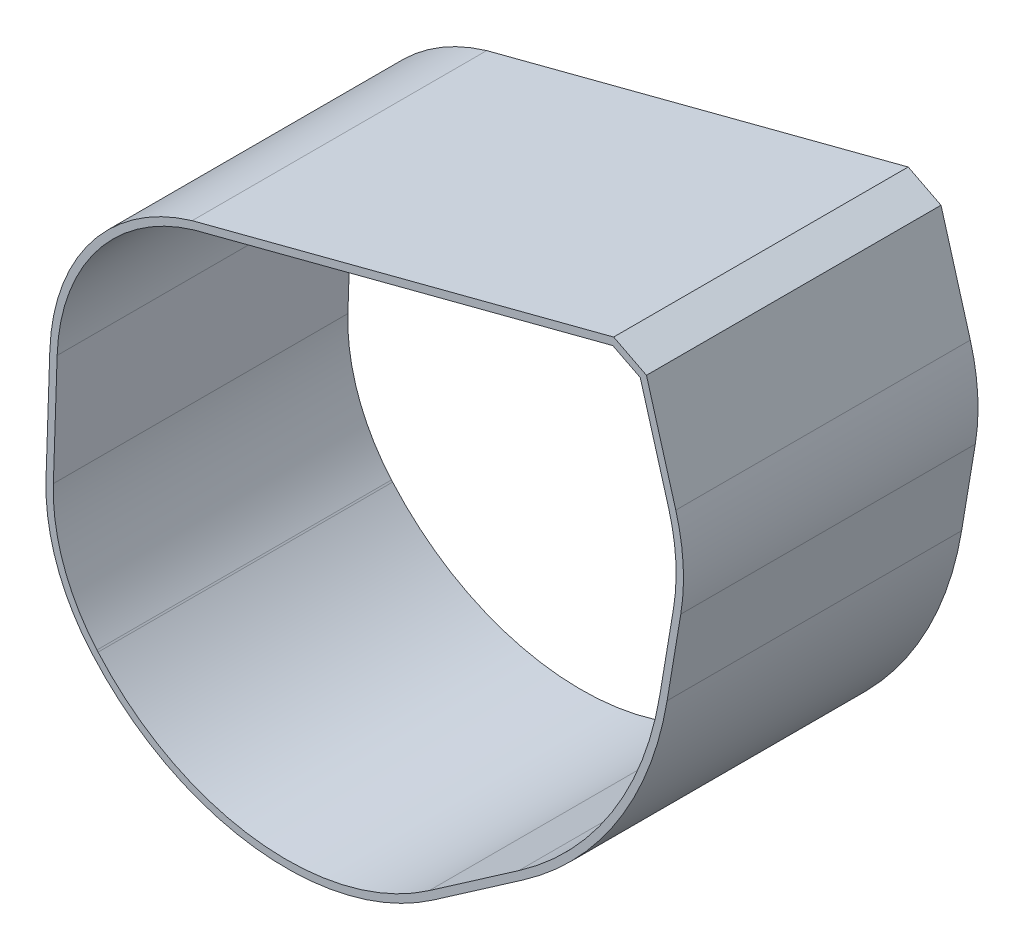
SolidWorks part; units mm, degrees
ref_plane "Front Plane" through (0, 0, 0) normal (0, 0, 1) x (1, 0, 0)
ref_plane "Top Plane" through (0, 0, 0) normal (0, 1, 0) x (1, 0, 0)
ref_plane "Right Plane" through (0, 0, 0) normal (1, 0, 0) x (0, 0, -1)
sketch "Sketch1" plane through (0, 0, 0) normal (0, 0, 1) x (1, 0, 0)
  line L0 (77.6667, 150) -> (388.3333, 150) construction
  line L1 (52.4805, 258.675) -> (196.8948, 296.3428)
  line L3 (217.8369, 228.2504) -> (213.1205, 200.0364)
  line L4 (164.4487, 123.2792) -> (133.5605, 101.8652)
  line L5 (19.3436, 115.9934) -> (18.9488, 116.4449)
  line L6 (3.9153, 158.621) -> (5.2264, 197.5738)
  line L7 (196.8948, 296.3428) -> (206.3731, 291.5239)
  line L8 (206.3731, 291.5239) -> (216.1786, 257.3555)
  line L17 (51.7997, 261.1224) -> (197.1866, 299.0439)
  line L18 (197.1866, 299.0439) -> (208.5097, 293.2871)
  line L19 (208.5097, 293.2871) -> (218.6201, 258.0561)
  line L20 (220.3422, 227.8316) -> (215.6258, 199.6176)
  line L21 (165.8959, 121.1918) -> (135.0077, 99.7778)
  line L22 (17.4314, 114.3215) -> (17.0367, 114.773)
  line L23 (1.3768, 158.7064) -> (2.6879, 197.6592)
  arc A0 (52.4805, 258.675) -> (5.2264, 197.5738) centre (71.2291, 195.3522) ccw
  arc A1 (216.1786, 257.3555) -> (217.8369, 228.2504) centre (152.7008, 239.1389) cw
  arc A2 (213.1205, 200.0364) -> (164.4487, 123.2792) centre (97.8796, 219.3007) cw
  arc A3 (133.5605, 101.8652) -> (19.3436, 115.9934) centre (84.3573, 172.8377) cw
  arc A4 (18.9488, 116.4449) -> (3.9153, 158.621) centre (64.8408, 156.5703) cw
  arc A10 (218.6201, 258.0561) -> (220.3422, 227.8316) centre (152.7008, 239.1389) cw
  arc A11 (215.6258, 199.6176) -> (165.8959, 121.1918) centre (97.8796, 219.3007) cw
  arc A12 (135.0077, 99.7778) -> (17.4314, 114.3215) centre (84.3573, 172.8377) cw
  arc A13 (17.0367, 114.773) -> (1.3768, 158.7064) centre (64.8408, 156.5703) cw
  arc A14 (51.7997, 261.1224) -> (2.6879, 197.6592) centre (71.2291, 195.3522) ccw
  dimension "D1" = 66.04
  dimension "D4" = 86.36
  dimension "D5" = 60.96
  dimension "D7" = 2.54
extrude "Boss-Extrude1" add sketch "Sketch1" along normal blind 101.6
ref_plane "Plane1" through (0, 0, 76.2) normal (0, 0, 1) x (1, 0, 0)
